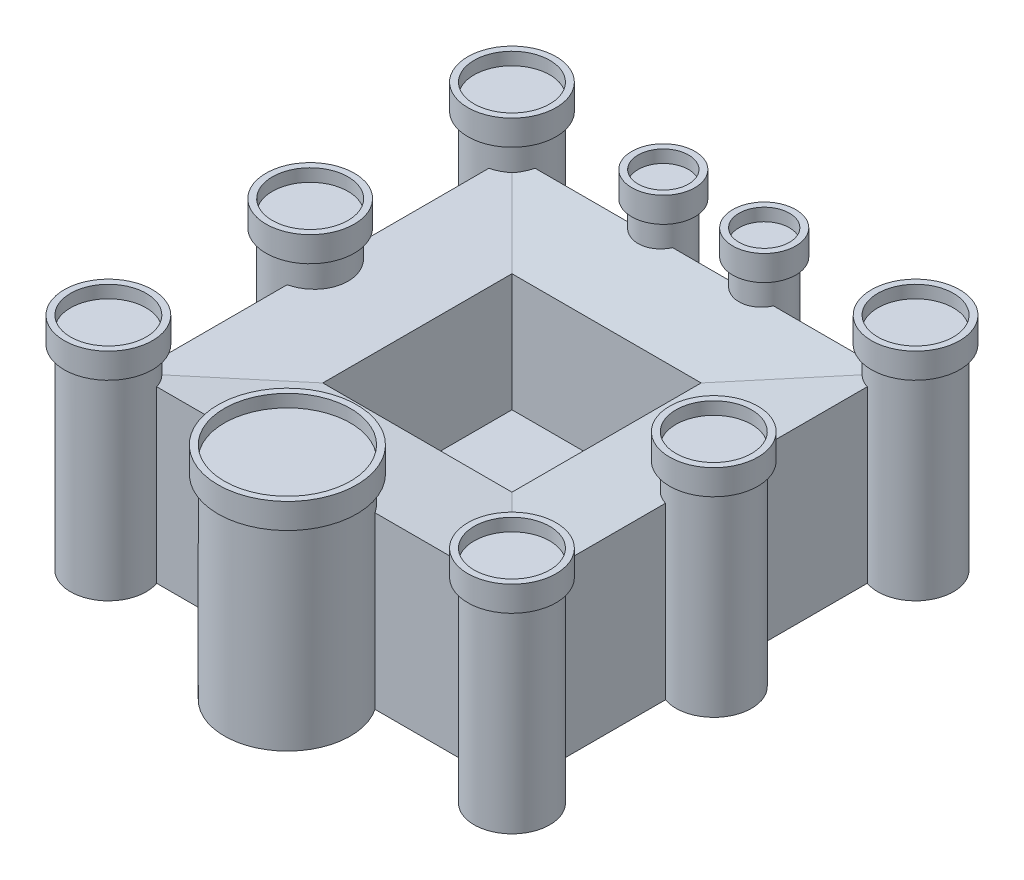
SolidWorks part; units mm, degrees
ref_plane "Alzado" through (0, 0, 0) normal (0, 0, 1) x (1, 0, 0)
ref_plane "Planta" through (0, 0, 0) normal (0, 1, 0) x (1, 0, 0)
ref_plane "Vista lateral" through (0, 0, 0) normal (1, 0, 0) x (0, 0, -1)
sketch "Croquis1" plane through (0, 0, 0) normal (0, 1, 0) x (1, 0, 0)
  line L1 (-15, -15) -> (15, -15)
  line L2 (-15, -15) -> (-15, 15)
  line L3 (-15, 15) -> (15, 15)
  line L4 (15, -15) -> (15, 15)
  line L5 (-15, -15) -> (15, 15) construction
  line L6 (-15, 15) -> (15, -15) construction
  point P0 (0, 0)
  dimension "D1" = 30
  dimension "D2" = 30
extrude "Saliente-Extruir1" add sketch "Croquis1" along normal blind 10
sketch "Croquis2" plane through (0, 10, 0) normal (0, 1, 0) x (1, 0, 0)
  line L1 (-7.5, -7.5) -> (7.5, -7.5)
  line L2 (-7.5, -7.5) -> (-7.5, 7.5)
  line L3 (-7.5, 7.5) -> (7.5, 7.5)
  line L12 (7.5, -7.5) -> (7.5, 7.5)
  line L13 (-7.5, -7.5) -> (7.5, 7.5) construction
  line L14 (-7.5, 7.5) -> (7.5, -7.5) construction
  point P2 (0, 0)
  dimension "D2" = 15
  dimension "D3" = 15
extrude "Cortar-Extruir2" cut sketch "Croquis2" against normal blind 10
sketch "Croquis3" plane through (0, 10, 0) normal (0, 1, 0) x (1, 0, 0)
  line L4 (15, -15) -> (15, 15)
  line L5 (15, 15) -> (-15, 15)
  line L6 (-15, 15) -> (-15, -15)
  line L7 (-15, -15) -> (15, -15)
  line L8 (15, -15) -> (15, 15)
  line L9 (15, 15) -> (-15, 15)
  line L10 (-15, 15) -> (-15, -15)
  line L11 (-15, -15) -> (15, -15)
  dimension "D1" = 0
extrude "Cortar-Extruir3" cut sketch "Croquis3" against normal blind 1 draft 85
sketch "Croquis4" plane through (0, 0, 0) normal (0, 1, 0) x (1, 0, 0)
  line L5 (0, 15) -> (0, 16) construction
  line L6 (15, 15) -> (-15, 15) construction
  line L7 (15, 0) -> (16, 0) construction
  line L8 (15, -15) -> (15, 15) construction
  line L9 (-15, 0) -> (-16, 0) construction
  line L10 (-15, 15) -> (-15, -15) construction
  line L11 (0, -15) -> (0, -16) construction
  line L12 (-15, -15) -> (15, -15) construction
  line L13 (-16, -16) -> (-16, 16) construction
  line L14 (-16, 16) -> (16, 16) construction
  line L15 (16, 16) -> (16, -16) construction
  line L16 (16, -16) -> (-16, -16) construction
  circle A10 centre (-16, 16) radius 3
  circle A11 centre (16, 16) radius 3
  circle A12 centre (16, 0) radius 3
  circle A13 centre (16, -16) radius 3
  circle A14 centre (-16, 0) radius 3
  circle A15 centre (-16, -16) radius 3
  circle A17 centre (-4, 16) radius 2
  circle A18 centre (4, 16) radius 2
  dimension "D1" = 1
  dimension "D2" = 1
  dimension "D5" = 1
  dimension "D3" = 1
  dimension "D4" = 1
extrude "Saliente-Extruir3" add sketch "Croquis4" along normal blind 12
sketch "Croquis5" plane through (0, 12, 0) normal (0, 1, 0) x (1, 0, 0)
  circle A16 centre (-16, 16) radius 3.5
  circle A17 centre (-4, 16) radius 2.5
  circle A18 centre (4, 16) radius 2.5
  circle A19 centre (16, 16) radius 3.5
  circle A20 centre (-16, 0) radius 3.5
  circle A21 centre (16, 0) radius 3.5
  circle A22 centre (16, -16) radius 3.5
  circle A23 centre (-16, -16) radius 3.5
extrude "Saliente-Extruir4" add sketch "Croquis5" along normal blind 2
sketch "Croquis6" plane through (0, 14, 0) normal (0, 1, 0) x (1, 0, 0)
  circle A17 centre (-16, -16) radius 3
  circle A18 centre (-16, 0) radius 3
  circle A19 centre (-16, 16) radius 3
  circle A20 centre (-4, 16) radius 2
  circle A21 centre (4, 16) radius 2
  circle A22 centre (16, 16) radius 3
  circle A23 centre (16, 0) radius 3
  circle A24 centre (16, -16) radius 3
extrude "Cortar-Extruir4" cut sketch "Croquis6" against normal blind 1
sketch "Croquis7" plane through (0, 0, -15) normal (0, 0, -1) x (-1, 0, 0)
  line L0 (-1.5, 0) -> (-1.5, 2)
  line L1 (0, 0) -> (0, 5.3356) construction
  line L2 (1.5, 2) -> (1.5, 0)
  line L3 (1.5, 5) -> (1.5, 3) construction
  line L4 (-1.5, 5) -> (-1.5, 3) construction
  line L5 (-2.2679, 0) -> (2.2679, 0) construction
  line L6 (-1.5, 0) -> (1.5, 0)
  spline S0 degree 2 poles (-1.5, 2) (-1.5, 3.25) (0, 5.3356) knots 0 0 0 1 1 1
  spline S1 degree 2 poles (1.5, 2) (1.5, 3.25) (0, 5.3356) knots 0 0 0 1 1 1
  point P12 (0, 5.3356)
  dimension "2" = 2
  dimension "D2" = 2
extrude "Cortar-Extruir5" cut sketch "Croquis7" against normal blind 1
sketch "Croquis8" plane through (0, 0, 0) normal (0, -1, 0) x (1, 0, 0)
  line L0 (15, 2.8284) -> (15, 13.1716)
  line L1 (-15, -15) -> (-5.7321, -15)
  line L2 (-15, -15) -> (-15, 13.1716)
  line L3 (-13.1716, 15) -> (13.1716, 15)
  line L4 (15, -13.1716) -> (15, -2.8284)
  line L5 (-15, -15) -> (0, 0) construction
  line L6 (0, 0) -> (15, -15) construction
  line L7 (5.7321, -15) -> (13.1716, -15)
  line L8 (-2.2679, -15) -> (2.2679, -15)
  line L12 (-1.5, -15) -> (-1.5, -14)
  line L13 (-1.5, -14) -> (1.5, -14)
  line L14 (1.5, -14) -> (1.5, -15)
  line L15 (1.5, -15) -> (2.2679, -15)
  line L16 (5.7321, -15) -> (13.1716, -15)
  line L17 (15, -13.1716) -> (15, -2.8284)
  line L18 (15, 2.8284) -> (15, 13.1716)
  line L19 (13.1716, 15) -> (-13.1716, 15)
  line L20 (-15, 13.1716) -> (-15, 2.8284)
  line L21 (-15, -2.8284) -> (-15, -13.1716)
  line L22 (-13.1716, -15) -> (-5.7321, -15)
  line L23 (-2.2679, -15) -> (-1.5, -15)
  line L24 (-1.5, -15) -> (-1.5, -14)
  line L25 (-1.5, -14) -> (1.5, -14)
  line L26 (1.5, -14) -> (1.5, -15)
  line L27 (1.5, -15) -> (2.2679, -15)
  line L28 (5.7321, -15) -> (13.1716, -15)
  line L29 (15, -13.1716) -> (15, -2.8284)
  line L30 (15, 2.8284) -> (15, 13.1716)
  line L31 (13.1716, 15) -> (-13.1716, 15)
  line L32 (-15, 13.1716) -> (-15, 2.8284)
  line L33 (-15, -2.8284) -> (-15, -13.1716)
  line L34 (-13.1716, -15) -> (-5.7321, -15)
  line L35 (-2.2679, -15) -> (-1.5, -15)
  arc A8 (2.2679, -15) -> (5.7321, -15) centre (4, -16) ccw
  arc A9 (13.1716, -15) -> (15, -13.1716) centre (16, -16) ccw
  arc A10 (15, -2.8284) -> (15, 2.8284) centre (16, 0) ccw
  arc A11 (15, 13.1716) -> (13.1716, 15) centre (16, 16) ccw
  arc A12 (-13.1716, 15) -> (-15, 13.1716) centre (-16, 16) ccw
  arc A13 (-15, 2.8284) -> (-15, -2.8284) centre (-16, 0) ccw
  arc A14 (-15, -13.1716) -> (-13.1716, -15) centre (-16, -16) ccw
  arc A15 (-5.7321, -15) -> (-2.2679, -15) centre (-4, -16) ccw
  arc A16 (2.2679, -15) -> (5.7321, -15) centre (4, -16) ccw
  arc A17 (13.1716, -15) -> (15, -13.1716) centre (16, -16) ccw
  arc A18 (15, -2.8284) -> (15, 2.8284) centre (16, 0) ccw
  arc A19 (15, 13.1716) -> (13.1716, 15) centre (16, 16) ccw
  arc A20 (-13.1716, 15) -> (-15, 13.1716) centre (-16, 16) ccw
  arc A21 (-15, 2.8284) -> (-15, -2.8284) centre (-16, 0) ccw
  arc A22 (-15, -13.1716) -> (-13.1716, -15) centre (-16, -16) ccw
  arc A23 (-5.7321, -15) -> (-2.2679, -15) centre (-4, -16) ccw
  point P8 (0, 0)
  dimension "D1" = 0
extrude "Saliente-Extruir5" add sketch "Croquis8" along normal blind 3.5 contours L24 L25 L26 L27 A16 L28 A17 L29 A18 L30 A19 L31 A20 L32 A21 L33 A22 L34 A23 L35
sketch "Croquis9" plane through (0, 0, 0) normal (0, 1, 0) x (1, 0, 0)
  circle A0 centre (0, -17.806) radius 5
extrude "Saliente-Extruir6" add sketch "Croquis9" along normal up to surface (12 mm away) up to face at (-16, 12, 19)
sketch "Croquis10" plane through (0, 12, 0) normal (0, 1, 0) x (1, 0, 0)
  circle A0 centre (0, -17.806) radius 5.5
extrude "Saliente-Extruir7" add sketch "Croquis10" along normal up to surface (2 mm away) up to face at (-16, 14, 19)
sketch "Croquis11" plane through (0, 14, 0) normal (0, 1, 0) x (1, 0, 0)
  circle A0 centre (0, -17.806) radius 5
extrude "Cortar-Extruir7" cut sketch "Croquis11" against normal up to surface (1 mm away) contours A0 up to face at (-16, 13, 19)
sketch "Croquis12" plane through (0, 0, 0) normal (0, -1, 0) x (1, 0, 0)
  line L1 (-4.1384, 15) -> (4.1384, 15)
  line L2 (-4.1384, 15) -> (4.1384, 15)
  arc A1 (4.1384, 15) -> (-4.1384, 15) centre (0, 17.806) ccw
  arc A2 (4.1384, 15) -> (-4.1384, 15) centre (0, 17.806) ccw
  dimension "D1" = 0
extrude "Saliente-Extruir8" add sketch "Croquis12" along normal up to surface (3.5 mm away) up to face at (0, -3.5, -6.2)
sketch "Croquis13" plane through (0, -3.5, 0) normal (0, -1, 0) x (1, 0, 0)
  circle A0 centre (0, 0) radius 1.6
extrude "Cortar-Extruir8" cut sketch "Croquis13" against normal blind 3
